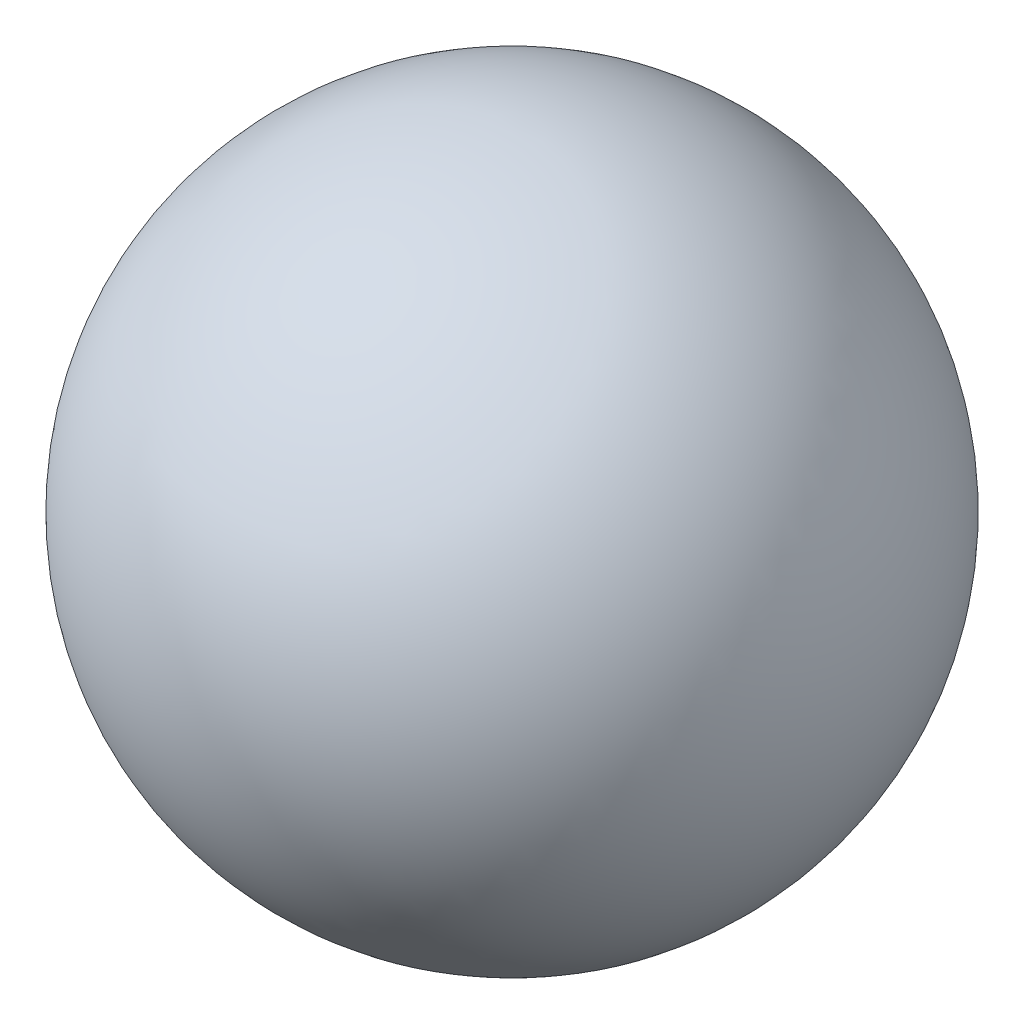
SolidWorks part; units mm, degrees
ref_plane "Front Plane" through (0, 0, 0) normal (0, 0, 1) x (1, 0, 0)
ref_plane "Top Plane" through (0, 0, 0) normal (0, 1, 0) x (1, 0, 0)
ref_plane "Right Plane" through (0, 0, 0) normal (1, 0, 0) x (0, 0, -1)
sketch "Sketch1" plane through (0, 0, 0) normal (0, 0, 1) x (1, 0, 0)
  line L0 (0, 3.5) -> (0, -3.5)
  arc A0 (0, -3.5) -> (0, 3.5) centre (0, 0) ccw
  dimension "D1" = 7
  dimension "D2" = 7
revolve "Revolve1" add sketch "Sketch1" angle 360 about L0
